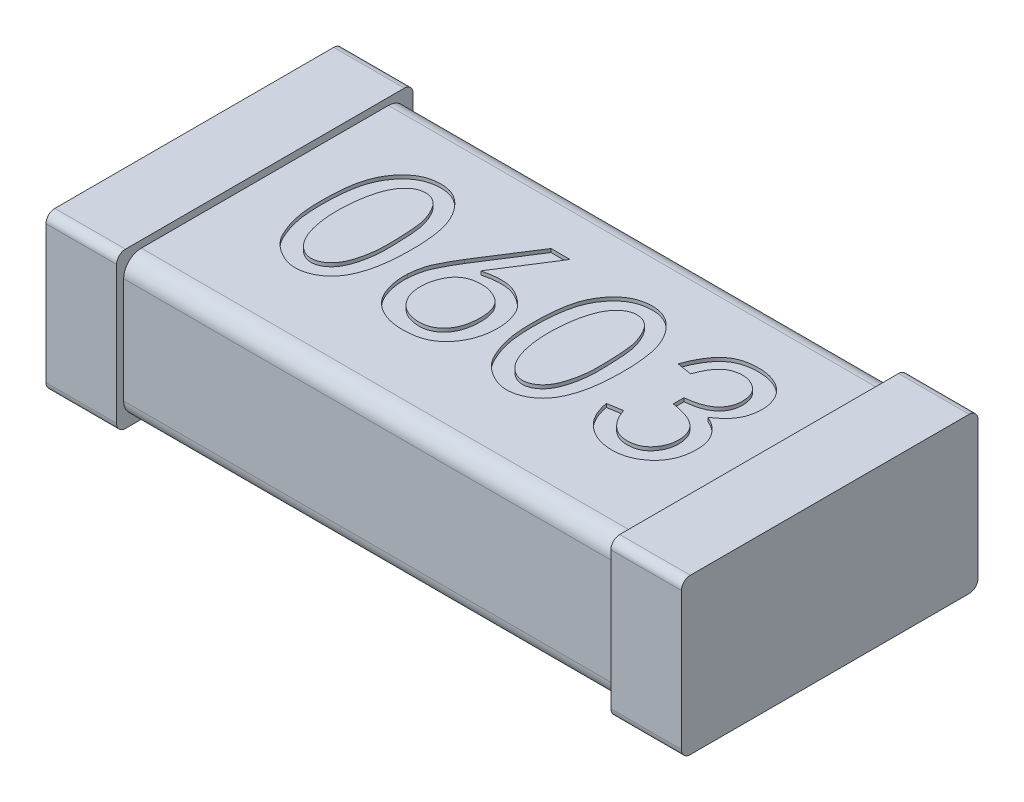
SolidWorks part; units mm, degrees
ref_plane "前视基准面" through (0, 0, 0) normal (0, 0, 1) x (1, 0, 0)
ref_plane "上视基准面" through (0, 0, 0) normal (0, 1, 0) x (1, 0, 0)
ref_plane "右视基准面" through (0, 0, 0) normal (1, 0, 0) x (0, 0, -1)
sketch "草图1" plane through (0, 0, 0) normal (0, 1, 0) x (1, 0, 0)
  line L0 (47.9534, 0) -> (-36.8195, 0) construction
  line L1 (-0.8, 0.4) -> (0.8, 0.4)
  line L2 (-0.8, 0.4) -> (-0.8, -0.4)
  line L3 (-0.8, -0.4) -> (0.8, -0.4)
  line L4 (0.8, 0.4) -> (0.8, -0.4)
  line L5 (0, 30.9913) -> (0, -28.7534) construction
  dimension "D1" = 0.8
  dimension "D2" = 1.6
extrude "凸台-拉伸1" add sketch "草图1" along normal blind 0.4
sketch "草图2" plane through (0.8, 0, 0) normal (1, 0, 0) x (0, 0, -1)
  line L0 (0, -0.0568) -> (0, 0.4756) construction
  line L1 (-0.395, 0.42) -> (0.395, 0.42)
  line L2 (-0.42, 0.395) -> (-0.42, 0.005)
  line L3 (-0.395, -0.02) -> (0.395, -0.02)
  line L4 (0.42, 0.395) -> (0.42, 0.005)
  line L5 (-0.4689, 0.2) -> (0.4817, 0.2) construction
  line L7 (-0.4, 0) -> (0.4, 0) construction
  arc A0 (-0.395, 0.42) -> (-0.42, 0.395) centre (-0.395, 0.395) ccw
  arc A1 (0.395, 0.42) -> (0.42, 0.395) centre (0.395, 0.395) cw
  arc A2 (-0.395, -0.02) -> (-0.42, 0.005) centre (-0.395, 0.005) cw
  arc A3 (0.395, -0.02) -> (0.42, 0.005) centre (0.395, 0.005) ccw
  dimension "D4" = 0.05
  dimension "D1" = 0.44
  dimension "D2" = 0.84
  dimension "D3" = 0.2
extrude "凸台-拉伸2" add sketch "草图2" against normal blind 0.2
sketch "草图4" plane through (-0.8, 0, 0) normal (-1, 0, 0) x (0, 0, 1)
  line L0 (-0.42, 0.005) -> (-0.42, 0.395) construction
  line L1 (0.395, -0.02) -> (-0.395, -0.02) construction
  line L2 (0.42, 0.395) -> (0.42, 0.005) construction
  line L3 (-0.395, 0.42) -> (0.395, 0.42) construction
  line L4 (-0.42, 0.005) -> (-0.42, 0.395)
  line L5 (0.395, -0.02) -> (-0.395, -0.02)
  line L6 (0.42, 0.395) -> (0.42, 0.005)
  line L7 (-0.395, 0.42) -> (0.395, 0.42)
  arc A0 (-0.395, 0.42) -> (-0.42, 0.395) centre (-0.395, 0.395) ccw construction
  arc A1 (-0.42, 0.005) -> (-0.395, -0.02) centre (-0.395, 0.005) ccw construction
  arc A2 (0.395, -0.02) -> (0.42, 0.005) centre (0.395, 0.005) ccw construction
  arc A3 (0.42, 0.395) -> (0.395, 0.42) centre (0.395, 0.395) ccw construction
  arc A4 (-0.395, 0.42) -> (-0.42, 0.395) centre (-0.395, 0.395) ccw
  arc A5 (-0.42, 0.005) -> (-0.395, -0.02) centre (-0.395, 0.005) ccw
  arc A6 (0.395, -0.02) -> (0.42, 0.005) centre (0.395, 0.005) ccw
  arc A7 (0.42, 0.395) -> (0.395, 0.42) centre (0.395, 0.395) ccw
extrude "凸台-拉伸3" add sketch "草图4" along normal blind 0.2
fillet "圆角1" radius 0.05 4 edges at (-0.1, 0, 0.4) (-0.1, 0, -0.4) (-0.1, 0.4, -0.4) (-0.1, 0.4, 0.4)
sketch "草图5" plane through (0, 0.4, 0) normal (0, 1, 0) x (1, 0, 0)
  text T0 "0603" font "黑体" height 0.4
extrude "切除-拉伸1" cut sketch "草图5" against normal blind 0.01
